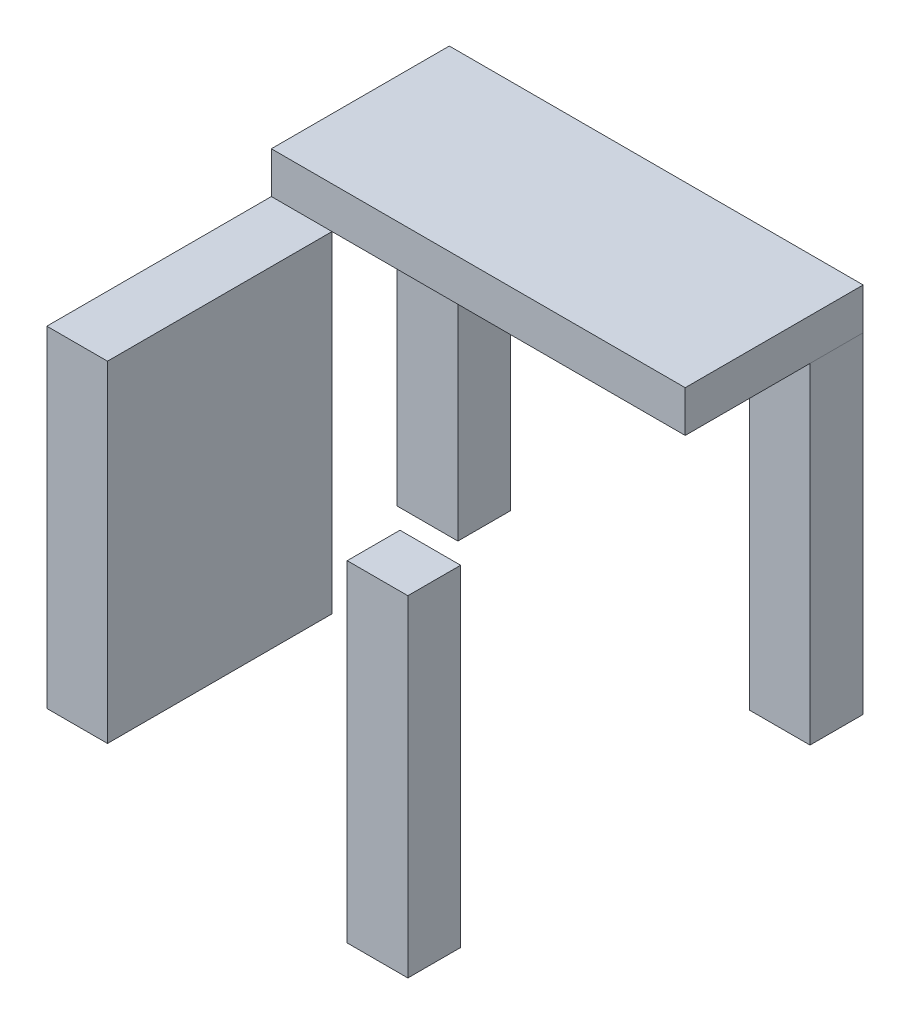
SolidWorks part; units mm, degrees
ref_plane "Front Plane" through (0, 0, 0) normal (0, 0, 1) x (1, 0, 0)
ref_plane "Top Plane" through (0, 0, 0) normal (0, 1, 0) x (1, 0, 0)
ref_plane "Right Plane" through (0, 0, 0) normal (1, 0, 0) x (0, 0, -1)
sketch "Sketch1" plane through (0, 0, 0) normal (0, 0, 1) x (1, 0, 0)
  line L1 (0, 0) -> (100, 0)
  line L2 (0, 0) -> (0, 10)
  line L3 (0, 10) -> (100, 10)
  line L4 (100, 0) -> (100, 10)
  dimension "D1" = 10
  dimension "D2" = 100
extrude "Boss-Extrude1" add sketch "Sketch1" along normal blind 43
sketch "Sketch2" plane through (0, 0, 0) normal (0, -1, 0) x (1, 0, 0)
  line L0 (85.3618, 110.0347) -> (100.0191, 110.0347)
  line L1 (0, 43) -> (14.6573, 43)
  line L2 (0, 43) -> (0, 97.2496)
  line L3 (0, 97.2496) -> (14.6573, 97.2496)
  line L4 (14.6573, 43) -> (14.6573, 97.2496)
  line L5 (85.3618, 110.0347) -> (85.3618, 97.2843)
  line L6 (85.3618, 97.2843) -> (100.0191, 97.2843)
  line L7 (100.0191, 110.0347) -> (100.0191, 97.2843)
  line L8 (-0.0191, 12.5688) -> (14.6382, 12.5688)
  line L9 (-0.0191, 12.5688) -> (-0.0191, -0.1816)
  line L10 (-0.0191, -0.1816) -> (14.6382, -0.1816)
  line L11 (14.6382, 12.5688) -> (14.6382, -0.1816)
  line L12 (85.2149, 12.7157) -> (99.8722, 12.7157)
  line L13 (85.2149, 12.7157) -> (85.2149, -0.0347)
  line L14 (85.2149, -0.0347) -> (99.8722, -0.0347)
  line L15 (99.8722, 12.7157) -> (99.8722, -0.0347)
extrude "Boss-Extrude2" add sketch "Sketch2" along normal blind 80
equation "\"LTest\" = 43mm"
equation "\"D1@Boss-Extrude1\"=\"LTest\""
